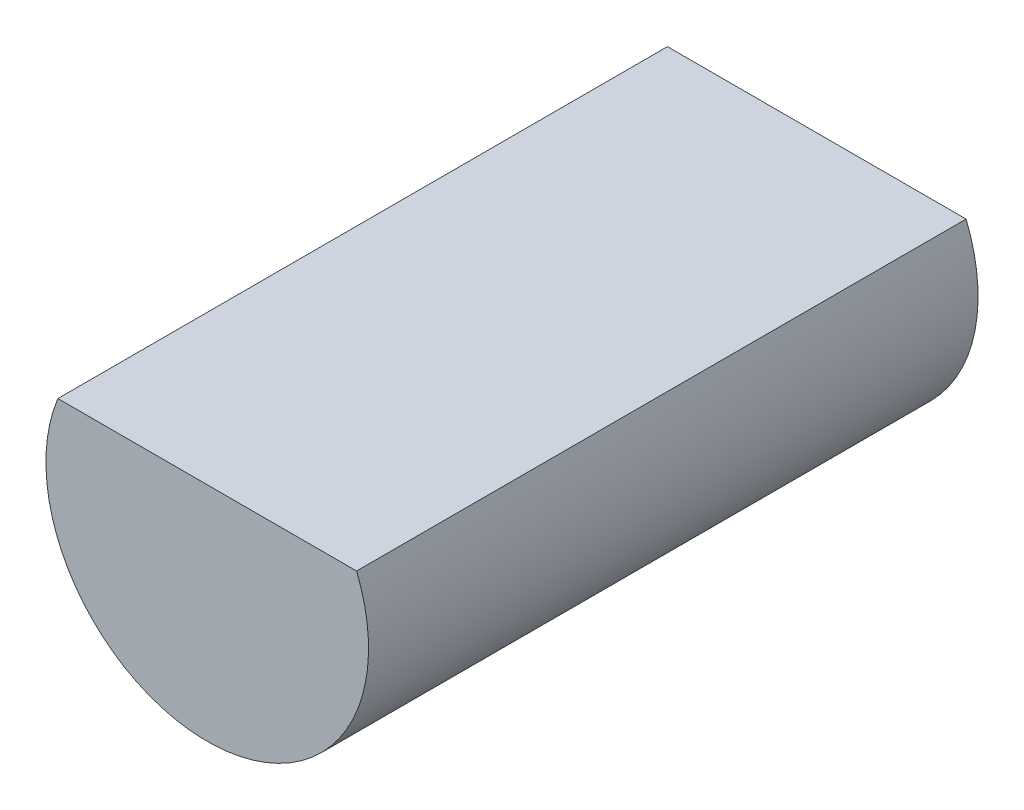
SolidWorks part; units mm, degrees
ref_plane "前视基准面" through (0, 0, 0) normal (0, 0, 1) x (1, 0, 0)
ref_plane "上视基准面" through (0, 0, 0) normal (0, 1, 0) x (1, 0, 0)
ref_plane "右视基准面" through (0, 0, 0) normal (1, 0, 0) x (0, 0, -1)
other "Configuration Table"
sketch "草图1" plane through (0, 0, 0) normal (0, 0, 1) x (1, 0, 0)
  line L0 (4.9, 2) -> (-4.9, 2)
  arc A0 (-4.9, 2) -> (4.9, 2) centre (0, 0) ccw
extrude "凸台-拉伸1" add sketch "草图1" along normal blind 20
